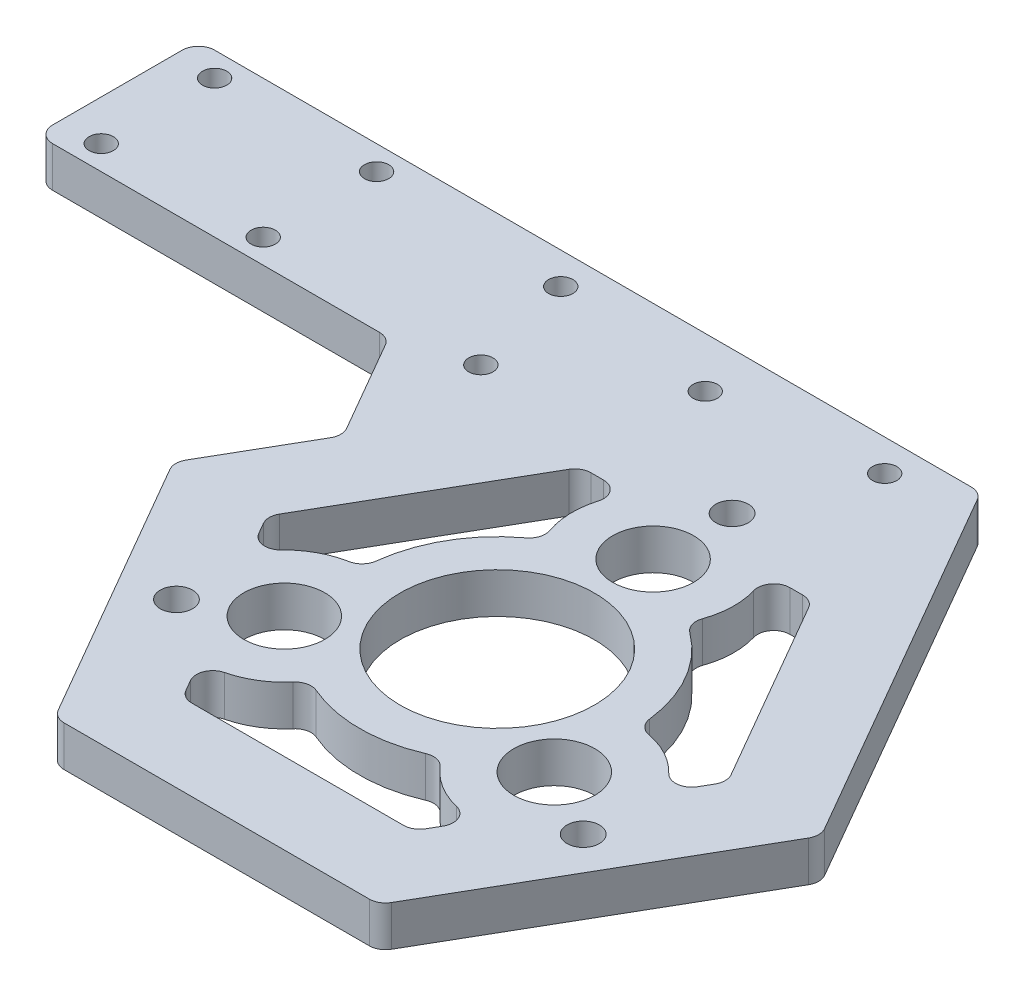
SolidWorks part; units mm, degrees
ref_plane "前视基准面" through (0, 0, 0) normal (0, 0, 1) x (1, 0, 0)
ref_plane "上视基准面" through (0, 0, 0) normal (0, 1, 0) x (1, 0, 0)
ref_plane "右视基准面" through (0, 0, 0) normal (1, 0, 0) x (0, 0, -1)
other "Configuration Table"
sketch "草图1" plane through (0, 0, 0) normal (0, 1, 0) x (1, 0, 0)
  line L8 (20, -34.641) -> (40, 0)
  line L9 (40, 0) -> (20, 34.641)
  line L10 (20, 34.641) -> (-4.6425, 34.641) construction
  line L11 (-20, 34.641) -> (-40, 0) construction
  line L12 (-40, 0) -> (-20, -34.641)
  line L13 (-20, -34.641) -> (20, -34.641)
  line L15 (-83.5, 26.6) -> (-40, 26.6)
  line L17 (-40, 0) -> (-32.3212, 13.3)
  line L18 (-32.3212, 13.3) -> (-40, 26.6)
  line L22 (0, 0) -> (-83.5, 0) construction
  line L23 (0, 0) -> (0, 26.6) construction
  line L24 (0, 26.6) -> (-83.5, 26.6) construction
  line L25 (-83.5, 26.6) -> (-83.5, 0) construction
  line L27 (13.0955, 46.6) -> (-83.5, 46.6)
  line L28 (-83.5, 46.6) -> (-83.5, 26.6)
  line L29 (-20, 34.641) -> (-4.6425, 34.641) construction
  line L30 (20, 34.641) -> (13.0955, 46.6)
  circle A0 centre (0, 0) radius 34.641 construction
  circle A1 centre (0, 0) radius 40 construction
  point P1 (11.815, 46.6)
  dimension "D1" = 80
  dimension "D2" = 26.6
  dimension "D3" = 120
  dimension "D4" = 20
  dimension "D5" = 43.5
extrude "凸台-拉伸1" add sketch "草图1" along normal blind 5
sketch "草图2" plane through (0, 5, 0) normal (0, 1, 0) x (1, 0, 0)
  line L0 (0, 19.25) -> (0, 0) construction
  circle A0 centre (0, 0) radius 29 construction
  circle A1 centre (0, 29) radius 2
  circle A2 centre (25.1147, -14.5) radius 2
  circle A3 centre (-25.1147, -14.5) radius 2
  circle A4 centre (0, 19.25) radius 5
  circle A5 centre (0, 0) radius 12
  circle A6 centre (0, 0) radius 19.25 construction
  circle A7 centre (16.671, -9.625) radius 5
  circle A8 centre (-16.671, -9.625) radius 5
  point P12 (0, 0)
  point P21 (0, 0)
  dimension "D1" = 58
  dimension "D2" = 4
  dimension "D4" = 10
  dimension "D6" = 24
  dimension "D5" = 19.25
  dimension "D3" = 3
  dimension "D7" = 3
extrude "切除-拉伸1" cut sketch "草图2" against normal through all
sketch "草图3" plane through (0, 0, 0) normal (0, -1, 0) x (1, 0, 0)
  line L0 (-78.5, -29.6) -> (-58.5, -29.6) construction
  line L1 (-83.5, -36.6) -> (18.869, -36.6) construction
  line L2 (-83.5, -46.6) -> (-83.5, -26.6) construction
  line L4 (-83.5, -26.6) -> (-40, -26.6) construction
  line L5 (40, 0) -> (13.0955, -46.6) construction
  circle A0 centre (-78.5, -29.6) radius 1.5
  circle A1 centre (-58.5, -29.6) radius 1.5
  circle A2 centre (-58.5, -43.6) radius 1.5
  circle A3 centre (-78.5, -43.6) radius 1.5
  point P8 (18.869, -36.6)
  dimension "D2" = 3
  dimension "D1" = 20
  dimension "D3" = 3
  dimension "D4" = 5
extrude "切除-拉伸2" cut sketch "草图3" against normal through all
sketch "草图4" plane through (0, 0, 0) normal (0, -1, 0) x (1, 0, 0)
  line L0 (-20, 34.641) -> (20, 34.641) construction
  line L1 (14.2265, 24.641) -> (-14.2265, 24.641)
  line L2 (-14.2265, 24.641) -> (-28.453, 0)
  line L3 (-28.453, 0) -> (-14.2265, -24.641)
  line L4 (-14.2265, -24.641) -> (14.2265, -24.641)
  line L5 (14.2265, -24.641) -> (28.453, 0)
  line L6 (28.453, 0) -> (14.2265, 24.641)
  line L7 (-25.1147, 14.5) -> (0, 0) construction
  line L8 (0, 0) -> (25.1147, 14.5) construction
  line L9 (0, 0) -> (0, -29) construction
  line L10 (-27.6147, 10.1699) -> (-2.5, -4.3301)
  line L11 (2.5, -4.3301) -> (27.6147, 10.1699)
  line L12 (-5, 0) -> (-5, -29)
  line L13 (-22.6147, 18.8301) -> (2.5, 4.3301)
  line L14 (-2.5, 4.3301) -> (22.6147, 18.8301)
  line L15 (5, 0) -> (5, -29)
  circle A0 centre (0, 0) radius 24.641 construction
  circle A1 centre (25.1147, 14.5) radius 7
  circle A2 centre (-25.1147, 14.5) radius 7
  circle A3 centre (0, -29) radius 7
  circle A4 centre (0, 0) radius 17
  circle A5 centre (0, -19.25) radius 10
  circle A6 centre (16.671, 9.625) radius 10
  circle A7 centre (-16.671, 9.625) radius 10
  dimension "D1" = 14
  dimension "D3" = 34
  dimension "D6" = 20
  dimension "D2" = 10
  dimension "D4" = 5
  dimension "D5" = 5
extrude "切除-拉伸4" cut sketch "草图4" against normal through all contours A7 L2 L3 L4 A5 A4 | A6 A4 A5 L4 L5 L6 | A7 A4 A6 L6 L1 L2
fillet "圆角1" radius 2 18 edges at (-14.2265, 2.5, 24.641) (14.2265, 2.5, 24.641) (-14.2265, 2.5, -24.641) (-28.453, 2.5, 0) (8.8182, 2.5, -14.5341) (-8.8182, 2.5, -14.5341) (8.4224, 2.5, -24.641) (-8.4224, 2.5, -24.641) (28.453, 2.5, 0) (14.2265, 2.5, -24.641) (17.1285, 2.5, 19.6145) (25.5509, 2.5, 5.0265) (8.1778, 2.5, 14.9038) (16.996, 2.5, -0.3697) (-8.1778, 2.5, 14.9038) (-16.996, 2.5, -0.3697) (-17.1285, 2.5, 19.6145) (-25.5509, 2.5, 5.0265)
fillet "圆角2" radius 2 9 edges at (40, 2.5, 0) (20, 2.5, 34.641) (-40, 2.5, 0) (-32.3212, 2.5, -13.3) (-40, 2.5, -26.6) (-83.5, 2.5, -26.6) (-83.5, 2.5, -46.6) (-20, 2.5, 34.641) (13.0955, 2.5, -46.6)
sketch "草图5" plane through (0, 0, 0) normal (0, -1, 0) x (1, 0, 0)
  line L0 (-31.4018, -29.3756) -> (0, 0) construction
  line L1 (0, 0) -> (-14.7167, -40.4032) construction
  line L2 (0, 0) -> (5.1521, -42.6902) construction
  line L7 (-37.3658, -22.0374) -> (11.1161, -50.0284) construction
  line L8 (-39.4226, -25.6) -> (-32.8986, -14.3) construction
  line L9 (39.4226, -1) -> (13.6728, -45.6) construction
  line L10 (-31.4018, -29.3756) -> (5.1521, -42.6902) construction
  line L11 (-34.8479, -42.6902) -> (5.1521, -42.6902) construction
  circle A1 centre (0, 0) radius 43 construction
  circle A2 centre (-31.4018, -29.3756) radius 1.5
  circle A3 centre (-14.7167, -40.4032) radius 1.5
  circle A4 centre (5.1521, -42.6902) radius 1.5
  circle A5 centre (-34.8479, -42.6902) radius 1.5
  point P10 (-13.1249, -36.0329)
  point P17 (-13.1249, -36.0329)
  point P18 (0, 0)
  dimension "D1" = 86
  dimension "D2" = 40
  dimension "D3" = 3
  dimension "D5" = 20
extrude "切除-拉伸5" cut sketch "草图5" against normal blind 10
